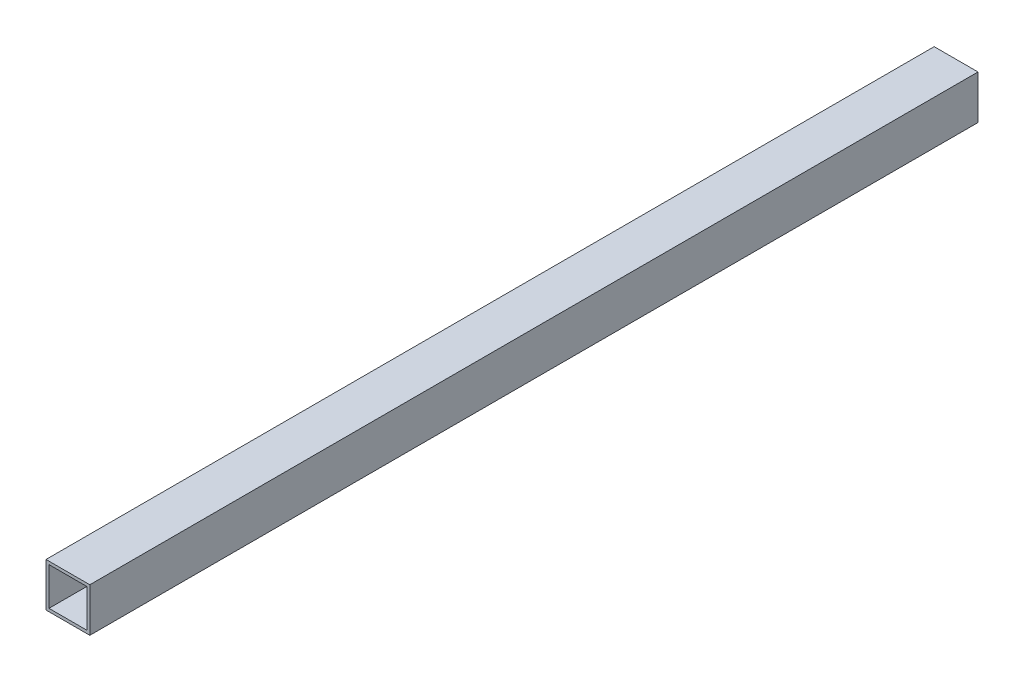
SolidWorks part; units mm, degrees
ref_plane "Front Plane" through (0, 0, 0) normal (0, 0, 1) x (1, 0, 0)
ref_plane "Top Plane" through (0, 0, 0) normal (0, 1, 0) x (1, 0, 0)
ref_plane "Right Plane" through (0, 0, 0) normal (1, 0, 0) x (0, 0, -1)
sketch "Sketch1" plane through (0, 0, 0) normal (0, 0, 1) x (1, 0, 0)
  line L0 (-6.4, 6.4) -> (6.4, 6.4)
  line L1 (-7.4, -7.4) -> (7.4, -7.4)
  line L2 (-7.4, -7.4) -> (-7.4, 7.4)
  line L3 (-7.4, 7.4) -> (7.4, 7.4)
  line L4 (7.4, -7.4) -> (7.4, 7.4)
  line L5 (-7.4, -7.4) -> (7.4, 7.4) construction
  line L6 (-7.4, 7.4) -> (7.4, -7.4) construction
  line L7 (6.4, -6.4) -> (6.4, 6.4)
  line L8 (-6.4, -6.4) -> (6.4, -6.4)
  line L9 (-6.4, -6.4) -> (-6.4, 6.4)
  point P0 (0, 0)
  dimension "D1" = 14.8
  dimension "D2" = 14.8
  dimension "D3" = 1
extrude "Boss-Extrude1" add sketch "Sketch1" along normal blind 300
